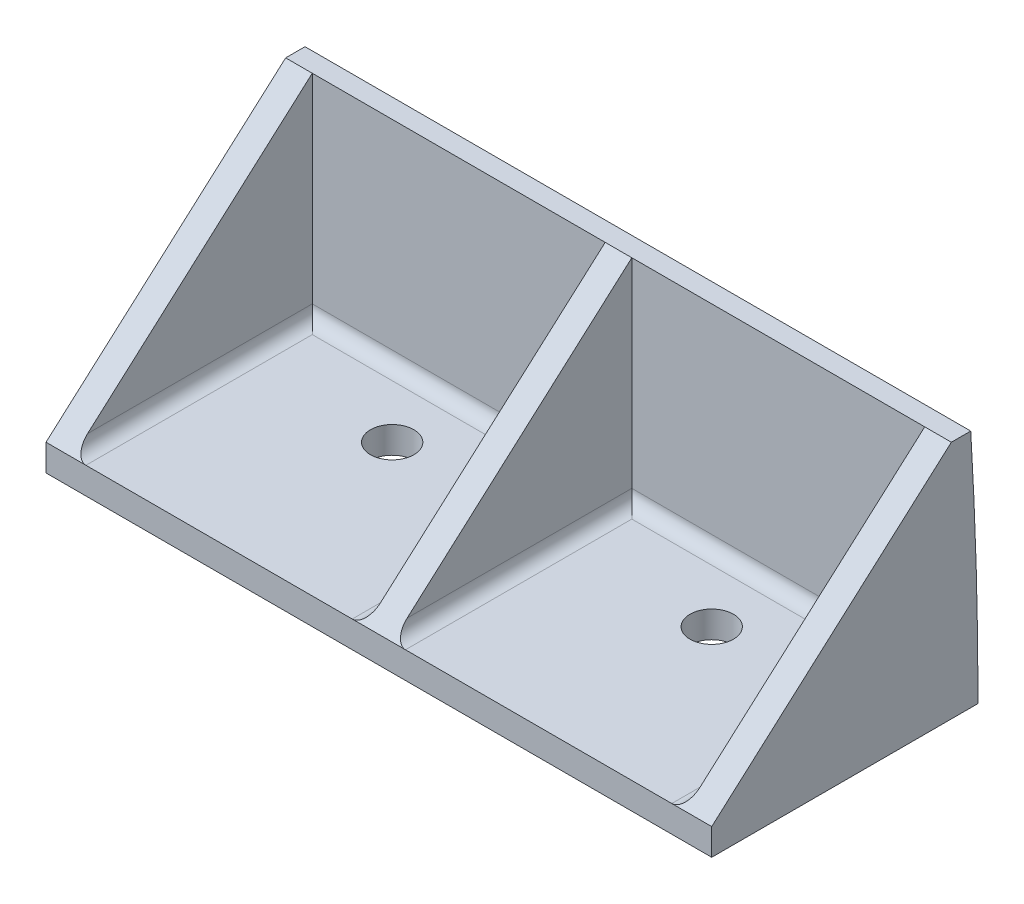
SolidWorks part; units mm, degrees
material "Alloy Steel"
ref_plane "Front Plane" through (0, 0, 0) normal (0, 0, 1) x (1, 0, 0)
ref_plane "Top Plane" through (0, 0, 0) normal (0, 1, 0) x (1, 0, 0)
ref_plane "Right Plane" through (0, 0, 0) normal (1, 0, 0) x (0, 0, -1)
sketch "Sketch5" plane through (0, 0, 0) normal (0, 1, 0) x (1, 0, 0)
  line L1 (-12.5, 10) -> (12.5, 10)
  line L2 (-12.5, 10) -> (-12.5, -10)
  line L3 (-12.5, -10) -> (12.5, -10)
  line L4 (12.5, 10) -> (12.5, -10)
  line L5 (-12.5, 10) -> (12.5, -10) construction
  line L6 (-12.5, -10) -> (12.5, 10) construction
  point P0 (0, 0)
  dimension "D1" = 20
  dimension "D2" = 25
extrude "Boss-Extrude3" add sketch "Sketch5" along normal blind 2
sketch "Sketch6" plane through (0, 2, 0) normal (0, 1, 0) x (1, 0, 0)
  line L0 (12.5, -10) -> (12.5, 10) construction
  line L1 (-12.5, 10) -> (12.5, 10)
  line L2 (-12.5, 10) -> (-12.5, 8)
  line L3 (-12.5, 8) -> (12.5, 8)
  line L4 (12.5, 10) -> (12.5, 8)
extrude "Boss-Extrude4" add sketch "Sketch6" along normal blind 16
sketch "Sketch7" plane through (12.5, 0, 0) normal (1, 0, 0) x (0, 0, -1)
  line L0 (8, 18) -> (-10, 2)
  line L1 (-10, 2) -> (8, 2)
  line L2 (8, 2) -> (8, 18)
extrude "Boss-Extrude5" add sketch "Sketch7" against normal blind 2
sketch "Sketch8" plane through (-12.5, 0, 0) normal (-1, 0, 0) x (0, 0, 1)
  line L0 (-8, 18) -> (-8, 2)
  line L1 (-8, 18) -> (-8, 2) construction
  line L2 (-8, 2) -> (10, 2)
  line L3 (10, 2) -> (-8, 18)
extrude "Boss-Extrude6" add sketch "Sketch8" against normal blind 1
sketch "Sketch9" plane through (0, 2, 0) normal (0, 1, 0) x (1, 0, 0)
  line L0 (-11.5, 3) -> (10.5, 3) construction
  line L3 (-11.5, 8) -> (-11.5, -10) construction
  line L4 (10.5, 8) -> (10.5, -10) construction
  line L5 (-11.5, 8) -> (10.5, 8) construction
  circle A0 centre (-0.5, 3) radius 1.63
  point P6 (-0.5, 3)
  point P9 (-0.5, 1.1381)
  point P10 (-0.5, 3.6771)
  dimension "D1" = 3.26
  dimension "D2" = 5
extrude "Cut-Extrude2" cut sketch "Sketch9" against normal through all and the other way through all
fillet "Fillet1" radius 1 3 edges at (-11.5, 2, 1) (10.5, 2, 1) (-0.5, 2, -8)
sketch "Sketch10" plane through (12.5, 0, 0) normal (1, 0, 0) x (0, 0, -1)
  line L0 (10, 0) -> (-287, 0) construction
  circle A0 centre (-287, 0) radius 297
  circle A1 centre (-287, 0) radius 307
  point P5 (-287, 0)
  dimension "D2" = 10
  dimension "D1" = 297
extrude "Cut-Extrude3" cut sketch "Sketch10" against normal through all
mirror "Mirror3" about plane through (-12.5, 2, -10) normal (1, 0, 0) of "Boss-Extrude4", "Boss-Extrude3", "Boss-Extrude5", "Boss-Extrude6", "Cut-Extrude2", "Fillet1", "Cut-Extrude3"
equation "\"BracketLength\"= 50mm"
equation "\"BracketWidth\"= 20mm"
equation "\"BracketHeight\"= 10mm"
equation "\"PlateThickness\"= 2mm"
equation "\"D1@Sketch5\"=\"BracketWidth\""
equation "\"D2@Sketch5\"=\"BracketLength\"/2"
equation "\"D1@Boss-Extrude3\"=\"PlateThickness\""
equation "\"D1@Sketch6\"=\"PlateThickness\""
equation "\"D1@Boss-Extrude4\"=2*\"BracketHeight\"-\"PlateThickness\"-2"
equation "\"D1@Boss-Extrude5\"=\"PlateThickness\""
equation "\"D1@Boss-Extrude6\"=\"PlateThickness\"/2"
equation "\"RivetHoleDiameter\"= 3.26mm"
equation "\"D1@Sketch9\"=\"RivetHoleDiameter\""
equation "\"RivetStandoff\"= 5mm"
equation "\"D2@Sketch9\"=\"RivetStandoff\""
